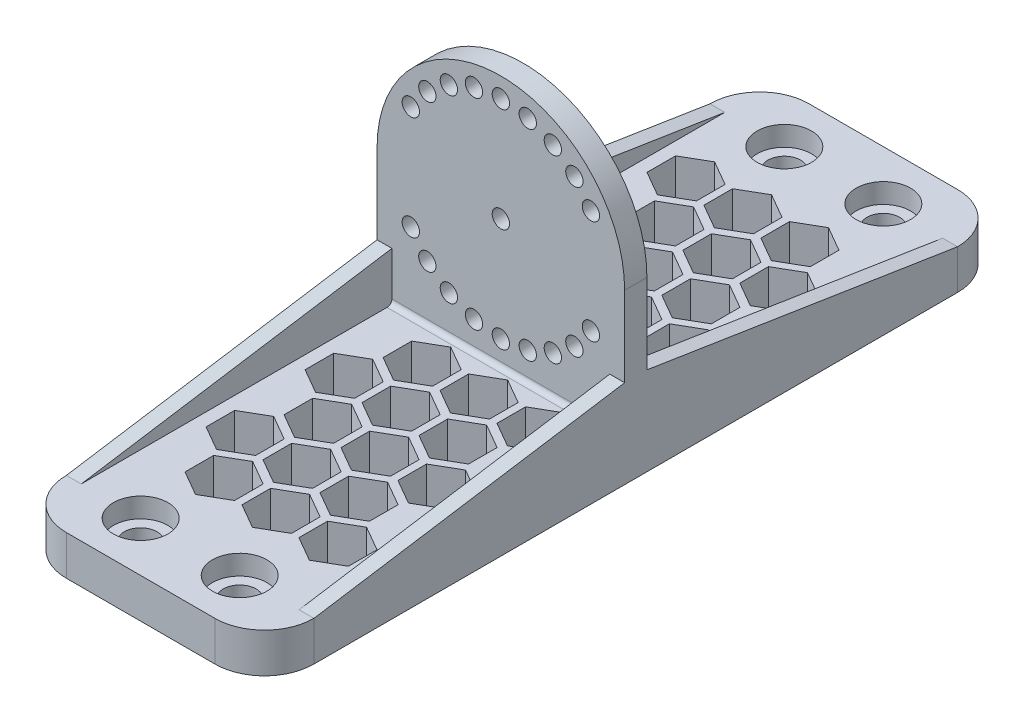
SolidWorks part; units mm, degrees
ref_plane "正面" through (0, 0, 0) normal (0, 0, 1) x (1, 0, 0)
ref_plane "平面" through (0, 0, 0) normal (0, 1, 0) x (1, 0, 0)
ref_plane "右側面" through (0, 0, 0) normal (1, 0, 0) x (0, 0, -1)
sketch "ｽｹｯﾁ1" plane through (0, 0, 0) normal (0, 1, 0) x (1, 0, 0)
  line L1 (25, 75) -> (-25, 75)
  line L2 (25, 75) -> (25, -75)
  line L3 (25, -75) -> (-25, -75)
  line L4 (-25, 75) -> (-25, -75)
  line L5 (25, 75) -> (-25, -75) construction
  line L6 (25, -75) -> (-25, 75) construction
  point P0 (0, 0)
  dimension "D1" = 150
  dimension "D2" = 50
extrude "ﾎﾞｽ - 押し出し1" add sketch "ｽｹｯﾁ1" along normal blind 8
sketch "ｽｹｯﾁ2" plane through (0, 0, 0) normal (0, 0, 1) x (1, 0, 0)
  line L0 (25, 8) -> (-25, 8)
  line L1 (-25, 8) -> (25, 8)
  line L4 (-25, 34) -> (-25, 8)
  line L5 (-25, 8) -> (25, 8)
  line L6 (-12, 8) -> (6.5, 8)
  line L7 (-25, 8) -> (25, 8)
  line L8 (25, 34) -> (25, 8)
  arc A1 (25, 34) -> (-25, 34) centre (0, 34) ccw
  circle A2 centre (0, 34) radius 1.75
  dimension "D1" = 26
  dimension "D3" = 0
  dimension "D2" = 25
  dimension "D6" = 3.5
  dimension "D4" = 26
  dimension "D5" = 26
extrude "ﾎﾞｽ - 押し出し2" add sketch "ｽｹｯﾁ2" along normal mid plane 4.5 contours L8 A1 L4 L0 L5
sketch "ｽｹｯﾁ5" plane through (0, 0, 0) normal (0, 0, 1) x (1, 0, 0)
  circle A0 centre (0, 34) radius 21
  circle A1 centre (0, 55) radius 1.75
  circle A2 centre (5.4352, 54.2844) radius 1.75
  circle A3 centre (10.5, 52.1865) radius 1.75
  circle A4 centre (14.8492, 48.8492) radius 1.75
  circle A5 centre (18.1865, 44.5) radius 1.75
  circle A6 centre (20.2844, 39.4352) radius 1.75
  circle A7 centre (21, 34) radius 1.75
  circle A8 centre (20.2844, 28.5648) radius 1.75
  circle A9 centre (18.1865, 23.5) radius 1.75
  circle A10 centre (14.8492, 19.1508) radius 1.75
  circle A11 centre (10.5, 15.8135) radius 1.75
  circle A12 centre (5.4352, 13.7156) radius 1.75
  circle A13 centre (0, 13) radius 1.75
  circle A14 centre (-5.4352, 13.7156) radius 1.75
  circle A15 centre (-10.5, 15.8135) radius 1.75
  circle A16 centre (-14.8492, 19.1508) radius 1.75
  circle A17 centre (-18.1865, 23.5) radius 1.75
  circle A18 centre (-20.2844, 28.5648) radius 1.75
  circle A19 centre (-21, 34) radius 1.75
  circle A20 centre (-20.2844, 39.4352) radius 1.75
  circle A21 centre (-18.1865, 44.5) radius 1.75
  circle A22 centre (-14.8492, 48.8492) radius 1.75
  circle A23 centre (-10.5, 52.1865) radius 1.75
  circle A24 centre (-5.4352, 54.2844) radius 1.75
  point P54 (0, 34)
  dimension "D1" = 42
  dimension "D2" = 3.5
  dimension "D3" = 24
  dimension "D4" = 0
  dimension "D5" = 0
extrude "ｶｯﾄ - 押し出し1" cut sketch "ｽｹｯﾁ5" against normal through all both and the other way through all contours A1 | A24 | A23 | A22 | A21 | A2 | A3 | A4 | A5 | A13 | A14 | A15 | A16 | A12 | A11 | A10 | A9 | A17
sketch "ｽｹｯﾁ6" plane through (0, 0, 0) normal (0, 1, 0) x (1, 0, 0)
  line L0 (0, -75) -> (0, 75) construction
  line L1 (-25, -75) -> (25, -75) construction
  line L2 (25, 75) -> (-25, 75) construction
  line L3 (-25, 0) -> (25, 0) construction
  line L4 (-25, 75) -> (-25, -75) construction
  line L5 (25, -75) -> (25, 75) construction
  line L6 (-25, -75) -> (25, -75) construction
  circle A0 centre (-10, -65) radius 3.3
  circle A1 centre (10, -65) radius 3.3
  circle A2 centre (10, 65) radius 3.3
  circle A3 centre (-10, 65) radius 3.3
  dimension "D1" = 6.6
  dimension "D2" = 10
  dimension "D3" = 10
extrude "ｶｯﾄ - 押し出し3" cut sketch "ｽｹｯﾁ6" against normal blind 5 and the other way through all
fillet "ﾌｨﾚｯﾄ1" radius 10 4 edges at (-25, 4, 75) (-25, 4, -75) (25, 4, -75) (25, 4, 75)
sketch "ｽｹｯﾁ8" plane through (0, 8, 0) normal (0, 1, 0) x (1, 0, 0)
  line L0 (-25, 0) -> (25, 0) construction
  line L1 (-25, -2.25) -> (-25, 2.25) construction
  line L2 (25, -2.25) -> (25, 2.25) construction
  line L3 (0, 75) -> (0, -75) construction
  line L4 (15, 75) -> (-15, 75) construction
  line L5 (-15, -75) -> (15, -75) construction
  circle A0 centre (-10, -65) radius 5.5
  circle A1 centre (10, -65) radius 5.5
  circle A2 centre (10, 65) radius 5.5
  circle A3 centre (-10, 65) radius 5.5
  dimension "D1" = 11
extrude "ｶｯﾄ - 押し出し5" cut sketch "ｽｹｯﾁ8" against normal blind 4
sketch "ｽｹｯﾁ10" plane through (0, 0, 2.25) normal (0, 0, 1) x (1, 0, 0)
  line L0 (0, 34) -> (12.5, 12.3494)
  line L1 (0, 34) -> (25, 34)
  line L2 (12.5, 12.3494) -> (25, 19.5662)
  line L4 (25, 34) -> (25, 8) construction
  line L5 (0, 34) -> (0, 8) construction
  line L6 (25, 8) -> (22, 8)
  line L7 (25, 8) -> (25, 17.8342)
  line L8 (25, 17.8342) -> (22, 17.8342)
  line L9 (22, 8) -> (22, 17.8342)
  line L10 (25, 8) -> (-25, 8) construction
  line L11 (-22, 8) -> (-22, 17.8342)
  line L12 (-25, 8) -> (-22, 8)
  line L13 (-25, 8) -> (-25, 17.8342)
  line L14 (-25, 17.8342) -> (-22, 17.8342)
  line L15 (-12.5, 12.3494) -> (-25, 19.5662)
  circle A0 centre (0, 34) radius 25
  dimension "D1" = 50
  dimension "D2" = 60
  dimension "D3" = 90
  dimension "D4" = 3
sketch "ｽｹｯﾁ11" plane through (25, 0, 0) normal (1, 0, 0) x (0, 0, -1)
  line L0 (-2.25, 17.8342) -> (-65, 8)
  line L1 (-65, 8) -> (-2.25, 8)
  line L2 (-2.25, 8) -> (-2.25, 17.8342)
  line L3 (0, 0) -> (0, 34) construction
  line L4 (-65, 0) -> (65, 0) construction
  line L5 (-2.25, 34) -> (2.25, 34) construction
  line L6 (65, 8) -> (2.25, 8)
  line L7 (2.25, 8) -> (2.25, 17.8342)
  line L8 (2.25, 17.8342) -> (65, 8)
extrude "ﾎﾞｽ - 押し出し3" add sketch "ｽｹｯﾁ11" against normal blind 3
sketch "ｽｹｯﾁ12" plane through (-25, 0, 0) normal (-1, 0, 0) x (0, 0, 1)
  line L0 (2.25, 17.8342) -> (65, 8)
  line L1 (2.25, 8) -> (65, 8) construction
  line L2 (65, 0) -> (65, 8) construction
  line L3 (0, 0) -> (0, 34) construction
  line L4 (-65, 0) -> (65, 0) construction
  line L5 (2.25, 34) -> (-2.25, 34) construction
  line L6 (-2.25, 17.8342) -> (-65, 8)
  line L7 (-2.25, 17.8342) -> (-2.25, 8)
  line L8 (-2.25, 8) -> (-65, 8)
  line L9 (65, 8) -> (2.25, 8)
  line L10 (2.25, 8) -> (2.25, 17.8342)
extrude "ﾎﾞｽ - 押し出し4" add sketch "ｽｹｯﾁ12" against normal blind 3
fillet "ﾌｨﾚｯﾄ2" radius 1 2 edges
sketch "ｽｹｯﾁ14" plane through (0, 8, 0) normal (0, 1, 0) x (1, 0, 0)
  line L0 (-22, 65) -> (-22, 3.25) construction
  line L1 (-14.375, 3.75) -> (-9.375, 6.6368)
  line L2 (-9.375, 6.6368) -> (-9.375, 12.4103)
  line L3 (-9.375, 12.4103) -> (-14.375, 15.297)
  line L4 (-14.375, 15.297) -> (-19.375, 12.4103)
  line L5 (-19.375, 12.4103) -> (-19.375, 6.6368)
  line L6 (-19.375, 6.6368) -> (-14.375, 3.75)
  line L8 (22, 2.25) -> (-22, 2.25) construction
  circle A0 centre (-14.375, 9.5235) radius 5 construction
  dimension "D1" = 5
  dimension "D2" = 2.625
  dimension "D3" = 1.5
extrude "ｶｯﾄ - 押し出し7" cut sketch "ｽｹｯﾁ14" against normal blind 10
pattern_linear "直線ﾊﾟﾀｰﾝ2" count 5 spacing 10 along (0, 0, -1) count 6 spacing 5.75 along (1, 0, 0) skipping (0, 1), (0, 3), (0, 5), (1, 0), (1, 2), (1, 4), (2, 1), (2, 3), (2, 5), (3, 0), (3, 2), (3, 4), (4, 1), (4, 3), (4, 5) of "ｶｯﾄ - 押し出し7"
sketch "ｽｹｯﾁ15" plane through (0, 8, 0) normal (0, 1, 0) x (1, 0, 0)
  line L0 (-22, -2.25) -> (22, -2.25) construction
  line L1 (14.375, -15.297) -> (19.375, -12.4103)
  line L2 (19.375, -12.4103) -> (19.375, -6.6368)
  line L3 (19.375, -6.6368) -> (14.375, -3.75)
  line L4 (14.375, -3.75) -> (9.375, -6.6368)
  line L5 (9.375, -6.6368) -> (9.375, -12.4103)
  line L6 (9.375, -12.4103) -> (14.375, -15.297)
  line L7 (22, -65) -> (22, -3.25) construction
  circle A0 centre (14.375, -9.5235) radius 5 construction
  dimension "D1" = 10
  dimension "D2" = 1.5
  dimension "D3" = 2.625
extrude "ｶｯﾄ - 押し出し8" cut sketch "ｽｹｯﾁ15" against normal blind 10
pattern_linear "直線ﾊﾟﾀｰﾝ3" count 5 spacing 10 along (0, 0, 1) count 6 spacing 5.75 along (-1, 0, 0) skipping (0, 1), (0, 3), (0, 5), (1, 0), (1, 2), (1, 4), (2, 1), (2, 3), (2, 5), (3, 0), (3, 2), (3, 4), (4, 1), (4, 3), (4, 5) of "ｶｯﾄ - 押し出し8"
